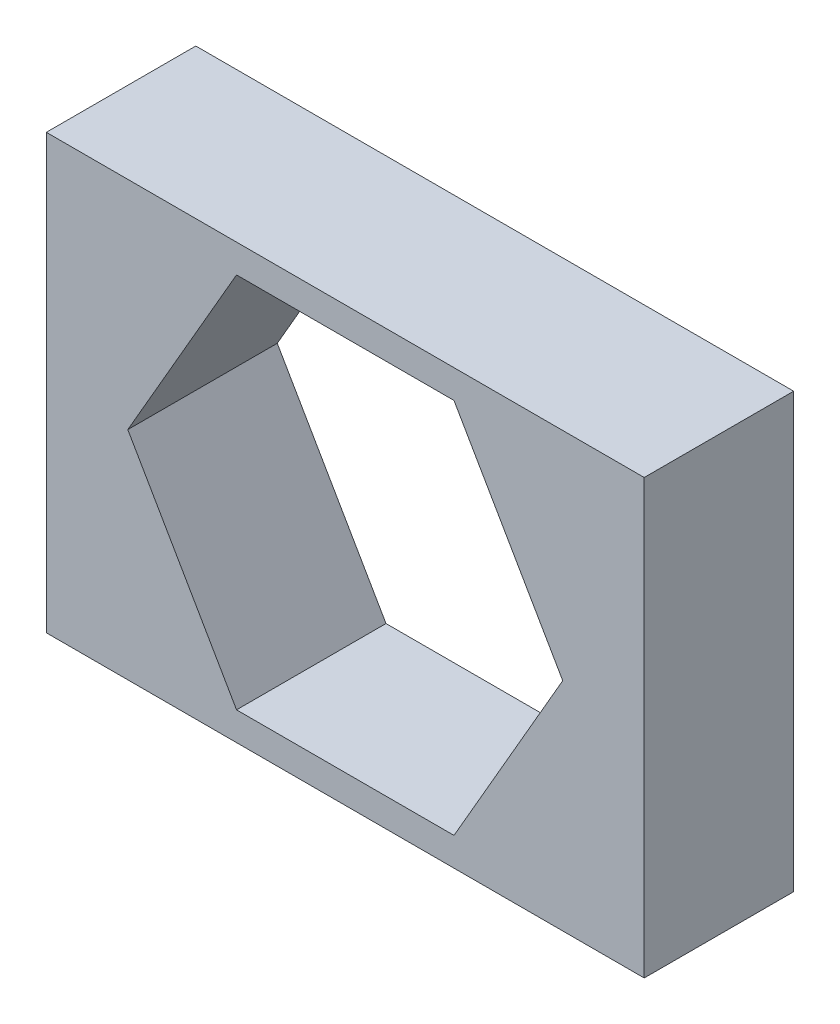
SolidWorks part; units mm, degrees
ref_plane "Plan de face" through (0, 0, 0) normal (0, 0, 1) x (1, 0, 0)
ref_plane "Plan de dessus" through (0, 0, 0) normal (0, 1, 0) x (1, 0, 0)
ref_plane "Plan de droite" through (0, 0, 0) normal (1, 0, 0) x (0, 0, -1)
sketch "Esquisse1" plane through (0, 0, 0) normal (0, 0, 1) x (1, 0, 0)
  line L0 (0, 7.25) -> (20, 7.25) construction
  line L1 (0, 0) -> (20, 0)
  line L2 (0, 0) -> (0, 14.5)
  line L3 (0, 14.5) -> (20, 14.5)
  line L4 (20, 0) -> (20, 14.5)
  line L6 (17.2746, 7.25) -> (13.6373, 13.55)
  line L7 (13.6373, 13.55) -> (6.3627, 13.55)
  line L8 (6.3627, 13.55) -> (2.7254, 7.25)
  line L9 (2.7254, 7.25) -> (6.3627, 0.95)
  line L10 (6.3627, 0.95) -> (13.6373, 0.95)
  line L11 (13.6373, 0.95) -> (17.2746, 7.25)
  circle A0 centre (10, 7.25) radius 6.3 construction
  dimension "D1" = 12.6
  dimension "D2" = 14.5
  dimension "D3" = 20
extrude "Boss.-Extru.1" add sketch "Esquisse1" along normal blind 5
